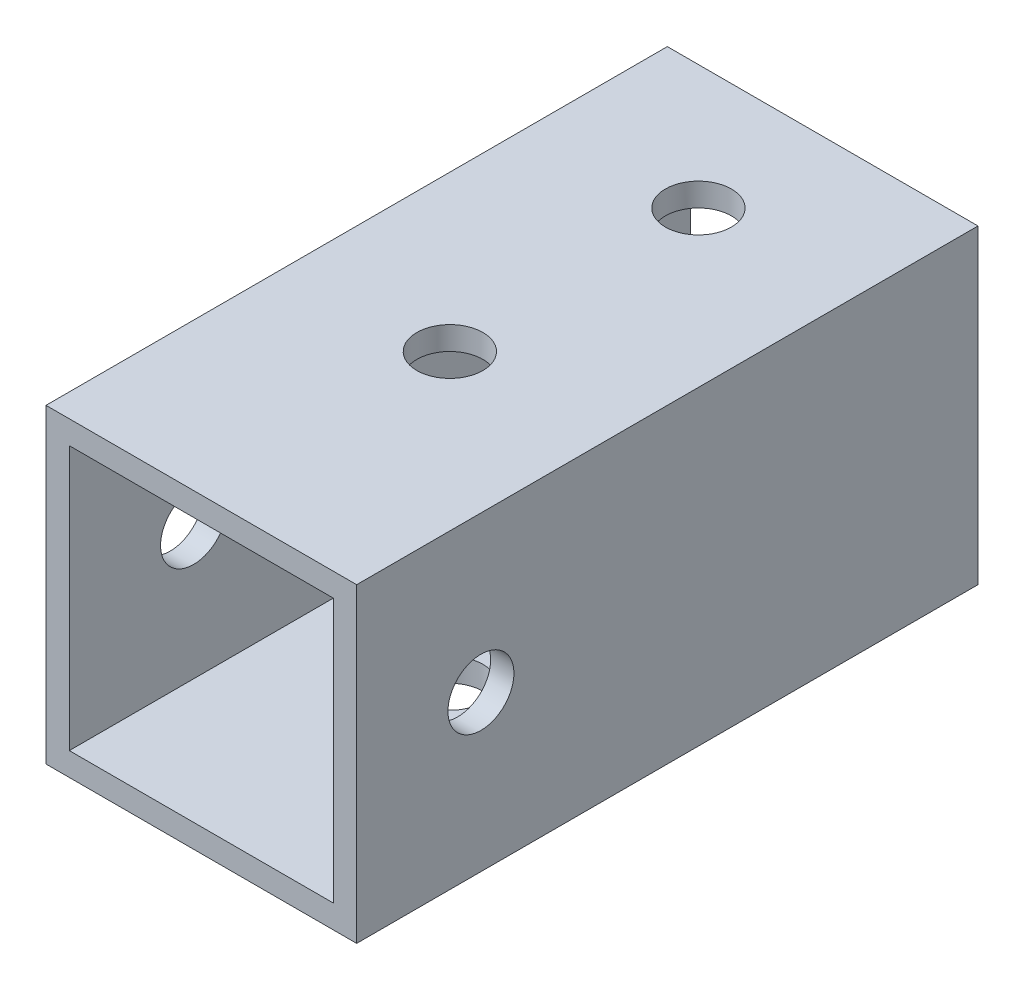
SolidWorks part; units mm, degrees
ref_plane "Front Plane" through (0, 0, 0) normal (0, 0, 1) x (1, 0, 0)
ref_plane "Top Plane" through (0, 0, 0) normal (0, 1, 0) x (1, 0, 0)
ref_plane "Right Plane" through (0, 0, 0) normal (1, 0, 0) x (0, 0, -1)
sketch "Sketch1" plane through (0, 0, 0) normal (0, 0, 1) x (1, 0, 0)
  line L0 (-8.5, -8.5) -> (8.5, -8.5)
  line L1 (-10, -10) -> (10, -10)
  line L2 (-10, -10) -> (-10, 10)
  line L3 (-10, 10) -> (10, 10)
  line L4 (10, -10) -> (10, 10)
  line L5 (-10, -10) -> (10, 10) construction
  line L6 (-10, 10) -> (10, -10) construction
  line L7 (8.5, -8.5) -> (8.5, 8.5)
  line L8 (-8.5, 8.5) -> (8.5, 8.5)
  line L9 (-8.5, -8.5) -> (-8.5, 8.5)
  point P0 (0, 0)
  dimension "D1" = 20
  dimension "D3" = 20
  dimension "D2" = 1.5
extrude "Boss-Extrude1" add sketch "Sketch1" against normal blind 40
sketch "Sketch2" plane through (0, 10, 0) normal (0, 1, 0) x (1, 0, 0)
  line L1 (0, 0) -> (0, 40) construction
  line L4 (10, 40) -> (-10, 40) construction
  circle A1 centre (0, 32) radius 2.125
  circle A2 centre (0, 16) radius 2.125
  dimension "D1" = 8
  dimension "D2" = 4.25
  dimension "D3" = 4.25
  dimension "D4" = 16
extrude "Cut-Extrude1" cut sketch "Sketch2" against normal through all
sketch "Sketch3" plane through (10, 0, 0) normal (1, 0, 0) x (0, 0, -1)
  line L0 (0, 0) -> (40, 0) construction
  line L3 (40, -10) -> (40, 10) construction
  line L4 (0, -10) -> (0, 10) construction
  circle A0 centre (8, 0) radius 2.125
  dimension "D1" = 4.25
  dimension "D2" = 8
extrude "Cut-Extrude2" cut sketch "Sketch3" against normal through all
